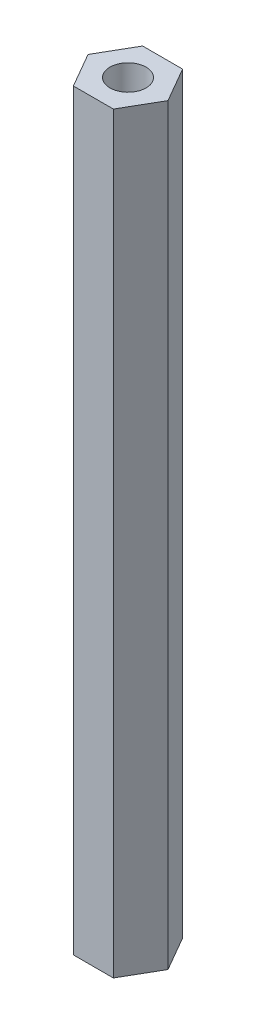
SolidWorks part; units mm, degrees
other "Markup1"
sketch "Sketch2" plane through (2.6558, 40, 2.3) normal (0.3825, 0.9065, 0.1787) x (0.7461, -0.1889, -0.6385)
ref_plane "Front Plane" through (0, 0, 0) normal (0, 0, 1) x (1, 0, 0)
ref_plane "Top Plane" through (0, 0, 0) normal (0, 1, 0) x (1, 0, 0)
ref_plane "Right Plane" through (0, 0, 0) normal (1, 0, 0) x (0, 0, -1)
sketch "Sketch1" plane through (0, 0, 0) normal (0, 1, 0) x (1, 0, 0)
  line L1 (2.6558, 0) -> (1.3279, 2.3)
  line L2 (1.3279, 2.3) -> (-1.3279, 2.3)
  line L3 (-1.3279, 2.3) -> (-2.6558, 0)
  line L4 (-2.6558, 0) -> (-1.3279, -2.3)
  line L5 (-1.3279, -2.3) -> (1.3279, -2.3)
  line L6 (1.3279, -2.3) -> (2.6558, 0)
  circle A0 centre (0, 0) radius 2.3 construction
  circle A2 centre (0, 0) radius 1.2
  dimension "D2" = 1.2
  dimension "D1" = 4.6
extrude "Boss-Extrude1" add sketch "Sketch1" along normal blind 50
